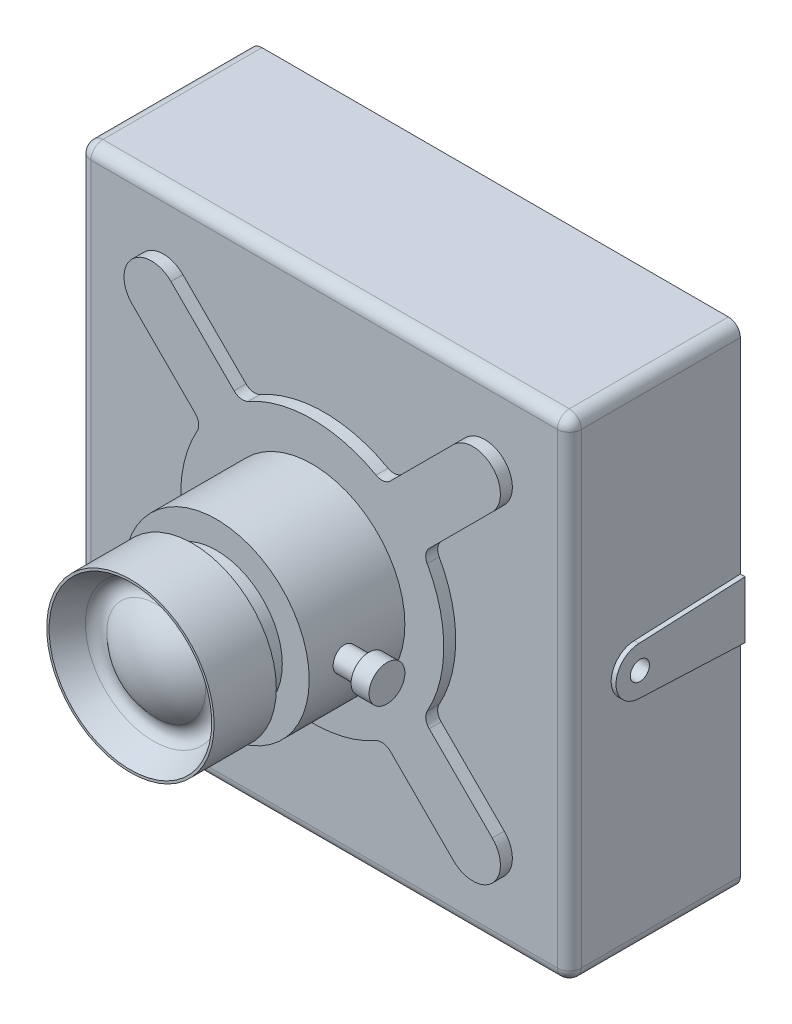
SolidWorks part; units mm, degrees
ref_plane "前视基准面" through (0, 0, 0) normal (0, 0, 1) x (1, 0, 0)
ref_plane "上视基准面" through (0, 0, 0) normal (0, 1, 0) x (1, 0, 0)
ref_plane "右视基准面" through (0, 0, 0) normal (1, 0, 0) x (0, 0, -1)
sketch "草图2" plane through (0, 0, 0) normal (0, 0, 1) x (1, 0, 0)
  line L1 (-20.5, -20.5) -> (20.5, -20.5)
  line L2 (-20.5, -20.5) -> (-20.5, 20.5)
  line L3 (-20.5, 20.5) -> (20.5, 20.5)
  line L4 (20.5, -20.5) -> (20.5, 20.5)
  line L5 (-20.5, -20.5) -> (20.5, 20.5) construction
  line L6 (-20.5, 20.5) -> (20.5, -20.5) construction
  point P0 (0, 0)
  dimension "D1" = 41
extrude "凸台-拉伸1" add sketch "草图2" along normal blind 14.3
sketch "草图3" plane through (0, 0, 14.3) normal (0, 0, 1) x (1, 0, 0)
  line L0 (-20.5, 20.5) -> (20.5, -20.5) construction
  line L1 (20.5, 20.5) -> (-20.5, -20.5) construction
  line L2 (-20.5, -20.5) -> (20.5, -20.5) construction
  line L3 (-20.5, 20.5) -> (-20.5, -20.5) construction
  line L4 (-11.8087, 15.0614) -> (-6.5318, 9.7845)
  line L5 (-15.0614, 11.8087) -> (-9.7845, 6.5318)
  line L6 (11.8087, 15.0614) -> (6.5318, 9.7845)
  line L7 (15.0614, 11.8087) -> (9.7845, 6.5318)
  line L8 (22.1263, 18.8737) -> (-18.8737, -22.1263) construction
  line L9 (18.8737, 22.1263) -> (-22.1263, -18.8737) construction
  line L10 (-18.8737, 22.1263) -> (22.1263, -18.8737) construction
  line L11 (-22.1263, 18.8737) -> (18.8737, -22.1263) construction
  line L12 (9.7845, -6.5318) -> (15.0614, -11.8087)
  line L13 (-6.5318, -9.7845) -> (-11.8087, -15.0614)
  line L14 (-9.7845, -6.5318) -> (-15.0614, -11.8087)
  line L15 (6.5318, -9.7845) -> (11.8087, -15.0614)
  arc A0 (-5.3393, -9.6173) -> (5.3393, -9.6173) centre (0, 0) ccw
  arc A1 (-15.0614, 11.8087) -> (-11.8087, 15.0614) centre (-13.435, 13.435) cw
  arc A2 (11.8087, 15.0614) -> (15.0614, 11.8087) centre (13.435, 13.435) cw
  arc A3 (11.8087, -15.0614) -> (15.0614, -11.8087) centre (13.435, -13.435) ccw
  arc A4 (-15.0614, -11.8087) -> (-11.8087, -15.0614) centre (-13.435, -13.435) ccw
  arc A5 (-9.6173, 5.3393) -> (-9.6173, -5.3393) centre (0, 0) ccw
  arc A6 (5.3393, 9.6173) -> (-5.3393, 9.6173) centre (0, 0) ccw
  arc A7 (9.6173, -5.3393) -> (9.6173, 5.3393) centre (0, 0) ccw
  arc A8 (-9.7845, -6.5318) -> (-9.6173, -5.3393) centre (-10.4916, -5.8247) ccw
  arc A9 (-6.5318, -9.7845) -> (-5.3393, -9.6173) centre (-5.8247, -10.4916) cw
  arc A10 (6.5318, -9.7845) -> (5.3393, -9.6173) centre (5.8247, -10.4916) ccw
  arc A11 (9.7845, -6.5318) -> (9.6173, -5.3393) centre (10.4916, -5.8247) cw
  arc A12 (9.7845, 6.5318) -> (9.6173, 5.3393) centre (10.4916, 5.8247) ccw
  arc A13 (6.5318, 9.7845) -> (5.3393, 9.6173) centre (5.8247, 10.4916) cw
  arc A14 (-6.5318, 9.7845) -> (-5.3393, 9.6173) centre (-5.8247, 10.4916) ccw
  arc A15 (-9.7845, 6.5318) -> (-9.6173, 5.3393) centre (-10.4916, 5.8247) cw
  point P34 (-14.5764, 14.5764)
  point P36 (0, 0)
  point P44 (0, 0)
  point P45 (0, 0)
  point P53 (9.2326, -5.9799)
  point P58 (5.9799, 9.2326)
  point P63 (-9.2326, 5.9799)
  dimension "D1" = 22
  dimension "D7" = 1
  dimension "D6" = 38
  dimension "D2" = 2.3
  dimension "D3" = 2.3
  dimension "D4" = 2.3
  dimension "D5" = 2.3
extrude "凸台-拉伸2" add sketch "草图3" along normal blind 1
sketch "草图4" plane through (0, 0, 15.3) normal (0, 0, 1) x (1, 0, 0)
  circle A0 centre (0, 0) radius 7.75
  dimension "D1" = 15.5
extrude "凸台-拉伸3" add sketch "草图4" along normal blind 8
sketch "草图5" plane through (0, 0, 23.3) normal (0, 0, 1) x (1, 0, 0)
  circle A0 centre (0, 0) radius 5.5
  dimension "D1" = 11
extrude "凸台-拉伸4" add sketch "草图5" along normal blind 2
sketch "草图6" plane through (0, 0, 25.3) normal (0, 0, 1) x (1, 0, 0)
  circle A0 centre (0, 0) radius 7
  dimension "D1" = 14
extrude "凸台-拉伸5" add sketch "草图6" along normal blind 5.2
sketch "草图7" plane through (0, 0, 0) normal (0, 1, 0) x (1, 0, 0)
  line L0 (-6.8, -30.5) -> (-5.6881, -28.5742)
  line L1 (-7, -30.5) -> (7, -30.5) construction
  line L2 (0, -30.5) -> (0, 0) construction
  line L3 (0, -30.5) -> (0, -30)
  line L4 (-6.8, -30.5) -> (0, -30.5)
  arc A0 (-4.1332, -28.3493) -> (0, -30) centre (0, -24) ccw
  arc A1 (-5.6881, -28.5742) -> (-4.1332, -28.3493) centre (-4.8221, -29.0742) cw
  dimension "D2" = 6
  dimension "D4" = 1
  dimension "D1" = 6.8
  dimension "D3" = 60
  dimension "D5" = 6.5
revolve "切除-旋转3" cut sketch "草图7" angle 360 about L2
fillet "圆角1" radius 1 8 edges at (-20.5, -20.5, 7.15) (-20.5, 0, 14.3) (0, -20.5, 14.3) (20.5, -20.5, 7.15) (20.5, 0, 14.3) (20.5, 20.5, 7.15) (0, 20.5, 14.3) (-20.5, 20.5, 7.15)
sketch "草图8" plane through (20.5, 0, 0) normal (1, 0, 0) x (0, 0, -1)
  line L0 (-8.8872, 1.9981) -> (0, 2.3861)
  line L1 (0, -19.5) -> (0, 19.5) construction
  line L2 (-8.8872, -1.9981) -> (0, -2.3861)
  line L3 (0, 2.3861) -> (0, -2.3861)
  line L4 (-8.8, 0) -> (0, 0) construction
  arc A0 (-8.8872, 1.9981) -> (-8.8872, -1.9981) centre (-8.8, 0) ccw
  dimension "D1" = 4
  dimension "D2" = 8.8
  dimension "D3" = 5
extrude "凸台-拉伸6" add sketch "草图8" along normal blind 0.4
hole_wizard "M2 螺纹孔1" positions "草图9" profile "草图10" tap size "M2" standard "GB"
sketch "草图9" plane through (20.9, 0, 0) normal (1, 0, 0) x (0, 0, -1)
  point P0 (-8.8, 0)
sketch "草图10" plane through (20.9, 0, 8.8) normal (0, 1, 0) x (0, 0, -1)
  line L0 (0, 0) -> (0, 5.6807)
  line L1 (0, 5.6807) -> (0.8, 5.2)
  line L2 (0.8, 5.2) -> (0.8, 0)
  line L5 (0.8, 0) -> (0, 0)
  line L10 (0, 5.6807) -> (-0.8, 5.2) construction
  line L11 (0, -6.35) -> (0, 107.95) construction
  dimension "螺纹孔钻头直径" = 1.6
  dimension "螺纹孔钻头深度" = 5.2
  dimension "导头角度" = 118
cosmetic thread "孔螺蚊线1" parameters "D1"=4, "D2"=2
mirror "镜向1" about plane through (0, 0, 0) normal (1, 0, 0) of "M2 螺纹孔1", "凸台-拉伸6"
sketch "草图11" plane through (0, 0, 0) normal (0, 0, -1) x (-1, 0, 0)
  line L0 (19.5, -20.5) -> (-19.5, -20.5) construction
  line L1 (-10.5, -11) -> (1, -11)
  line L2 (-10.5, -11) -> (-10.5, -17)
  line L3 (-10.5, -17) -> (1, -17)
  line L4 (1, -11) -> (1, -17)
  line L5 (-20.5, -19.5) -> (-20.5, -2.3861) construction
  dimension "D1" = 11.5
  dimension "D2" = 6
  dimension "D3" = 3.5
  dimension "D4" = 10
extrude "切除-拉伸1" cut sketch "草图11" against normal blind 7
sketch "草图12" plane through (0, 0, 7) normal (0, 0, -1) x (-1, 0, 0)
  line L0 (1, -11) -> (-10.5, -11) construction
  line L1 (-10.25, -11.2) -> (0.75, -11.2)
  line L2 (-10.25, -11.2) -> (-10.25, -16)
  line L3 (-10.25, -16) -> (0.75, -16)
  line L4 (0.75, -11.2) -> (0.75, -16)
  line L5 (1, -11) -> (-10.5, -11) construction
  point P4 (-4.75, -11.2)
  point P7 (-4.75, -11)
  point P8 (-10.25, -16.6077)
  dimension "D1" = 11
  dimension "D2" = 4.8
  dimension "D3" = 0.2
extrude "凸台-拉伸7" add sketch "草图12" along normal blind 8.5
sketch "草图13" plane through (0, 0, -1.5) normal (0, 0, -1) x (-1, 0, 0)
  line L0 (-8.56, -14) -> (-0.94, -14) construction
  line L1 (-10.25, -16) -> (0.75, -16) construction
  line L2 (-10.25, -16) -> (0.75, -16) construction
  circle A0 centre (-8.56, -14) radius 0.5
  circle A1 centre (-6.02, -14) radius 0.5
  circle A2 centre (-3.48, -14) radius 0.5
  circle A3 centre (-0.94, -14) radius 0.5
  point P8 (-5.9207, -12.8867)
  point P9 (-3.416, -12.8867)
  point P10 (-4.75, -14)
  point P13 (-4.75, -16)
  dimension "D1" = 2.54
  dimension "D2" = 2.54
  dimension "D3" = 2.54
  dimension "D5" = 1
  dimension "D4" = 2
extrude "凸台-拉伸8" add sketch "草图13" along normal blind 3
ref_plane "基准面1" through (7.75, 0, 0) normal (1, 0, 0) x (0, 0, -1)
sketch "草图14" plane through (7.75, 0, 0) normal (1, 0, 0) x (0, 0, -1)
  line L0 (-14.3, 5.3393) -> (-14.3, -5.3393) construction
  circle A0 centre (-20.3, 0) radius 1
  point P4 (0, 0)
  dimension "D1" = 6
  dimension "D2" = 2
extrude "凸台-拉伸9" add sketch "草图14" along normal blind 2 and the other way up to next
sketch "草图15" plane through (9.75, 0, 0) normal (1, 0, 0) x (0, 0, -1)
  circle A0 centre (-20.3, 0) radius 1.5
  dimension "D1" = 3
extrude "凸台-拉伸10" add sketch "草图15" along normal blind 1.5
